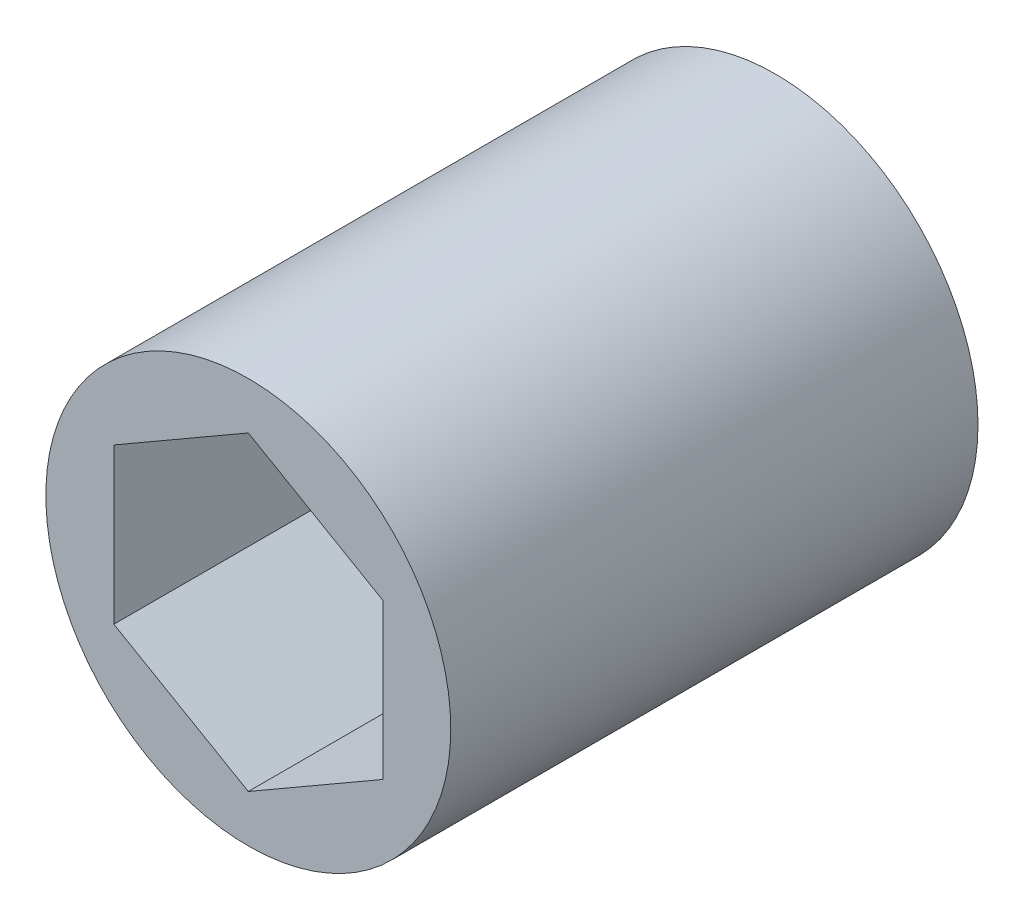
SolidWorks part; units mm, degrees
material "POM Acetal Copolymer"
ref_plane "Front" through (0, 0, 0) normal (0, 0, 1) x (1, 0, 0)
ref_plane "Top" through (0, 0, 0) normal (0, 1, 0) x (1, 0, 0)
ref_plane "Right" through (0, 0, 0) normal (1, 0, 0) x (0, 0, -1)
sketch "Sketch1" plane through (0, 0, 0) normal (0, 0, 1) x (1, 0, 0)
  line L1 (0, 7.479) -> (-6.477, 3.7395)
  line L2 (-6.477, 3.7395) -> (-6.477, -3.7395)
  line L3 (-6.477, -3.7395) -> (0, -7.479)
  line L4 (0, -7.479) -> (6.477, -3.7395)
  line L5 (6.477, -3.7395) -> (6.477, 3.7395)
  line L6 (6.477, 3.7395) -> (0, 7.479)
  circle A0 centre (0, 0) radius 9.7536
  circle A1 centre (0, 0) radius 6.477 construction
  dimension "D2" = 19.5072
  dimension "D1" = 12.954
extrude "Boss-Extrude1" add sketch "Sketch1" along normal blind 25.4
